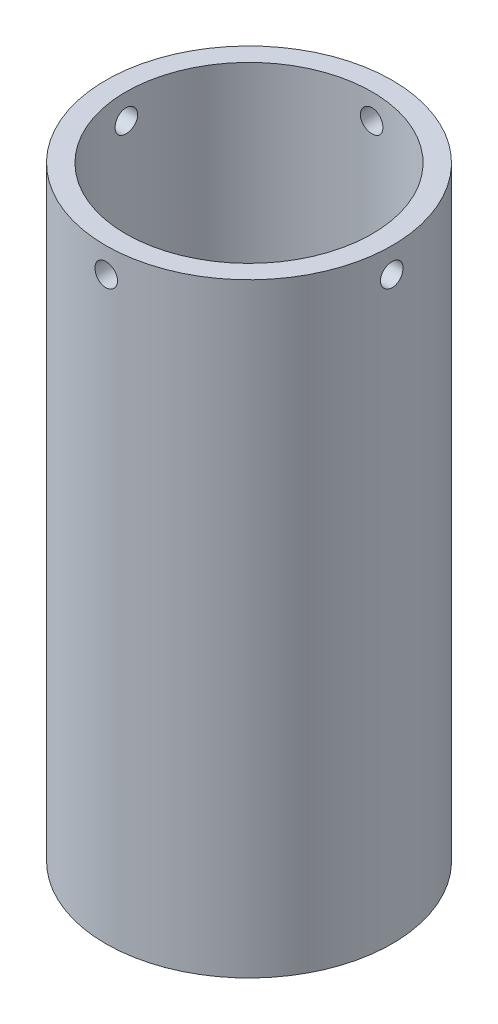
SolidWorks part; units mm, degrees
ref_plane "Front Plane" through (0, 0, 0) normal (0, 0, 1) x (1, 0, 0)
ref_plane "Top Plane" through (0, 0, 0) normal (0, 1, 0) x (1, 0, 0)
ref_plane "Right Plane" through (0, 0, 0) normal (1, 0, 0) x (0, 0, -1)
sketch "Sketch1" plane through (0, 0, 0) normal (0, 1, 0) x (1, 0, 0)
  circle A0 centre (0, 0) radius 28.5
  circle A1 centre (0, 0) radius 21
  dimension "D1" = 57
  dimension "D2" = 42
extrude "Boss-Extrude1" add sketch "Sketch1" along normal mid plane 121.35
sketch "Sketch2" plane through (0, 0, 0) normal (0, 0, 1) x (1, 0, 0)
  line L3 (21, 60.675) -> (-21, 60.675) construction
  circle A0 centre (0, 55.675) radius 2.25
  dimension "D1" = 4.5
  dimension "D2" = 5
extrude "Cut-Extrude1" cut sketch "Sketch2" against normal through all
pattern_circular "CirPattern1" count 4 every 90 about axis through (0, 60.675, 0) along (0, -1, 0) of "Cut-Extrude1"
sketch "Sketch5" plane through (0, -60.675, 0) normal (0, -1, 0) x (1, 0, 0)
  circle A0 centre (0, 0) radius 28.5 construction
  circle A1 centre (0, 0) radius 28.5
extrude "Cut-Extrude4" cut sketch "Sketch5" against normal blind 1
sketch "Sketch3" plane through (0, -59.675, 0) normal (0, -1, 0) x (1, 0, 0)
  line L0 (0, 28.5) -> (0, 21) construction
  arc A1 (2.25, 20.8791) -> (-2.25, 20.8791) centre (0, 0) ccw construction
  circle A2 centre (0, 24.75) radius 2.25
  circle A3 centre (24.75, 0) radius 2.25
  circle A4 centre (0, -24.75) radius 2.25
  circle A5 centre (-24.75, 0) radius 2.25
  circle A6 centre (0, 0) radius 28.5 construction
  point P2 (0, 30.0615)
  point P10 (0, 0)
  point P19 (0, 0)
  dimension "D1" = 4.5
  dimension "D2" = 4
extrude "Cut-Extrude2" cut sketch "Sketch3" against normal blind 6.5
sketch "Sketch4" plane through (0, 60.675, 0) normal (0, 1, 0) x (1, 0, 0)
  line L0 (0, 24.5) -> (0, 28.5) construction
  circle A0 centre (0, 0) radius 24.5
  circle A1 centre (0, 0) radius 28.5 construction
  dimension "D1" = 4
extrude "Cut-Extrude3" cut sketch "Sketch4" against normal offset from surface (109.85 mm away) 4 up to face at (0, -53.175, -27)
